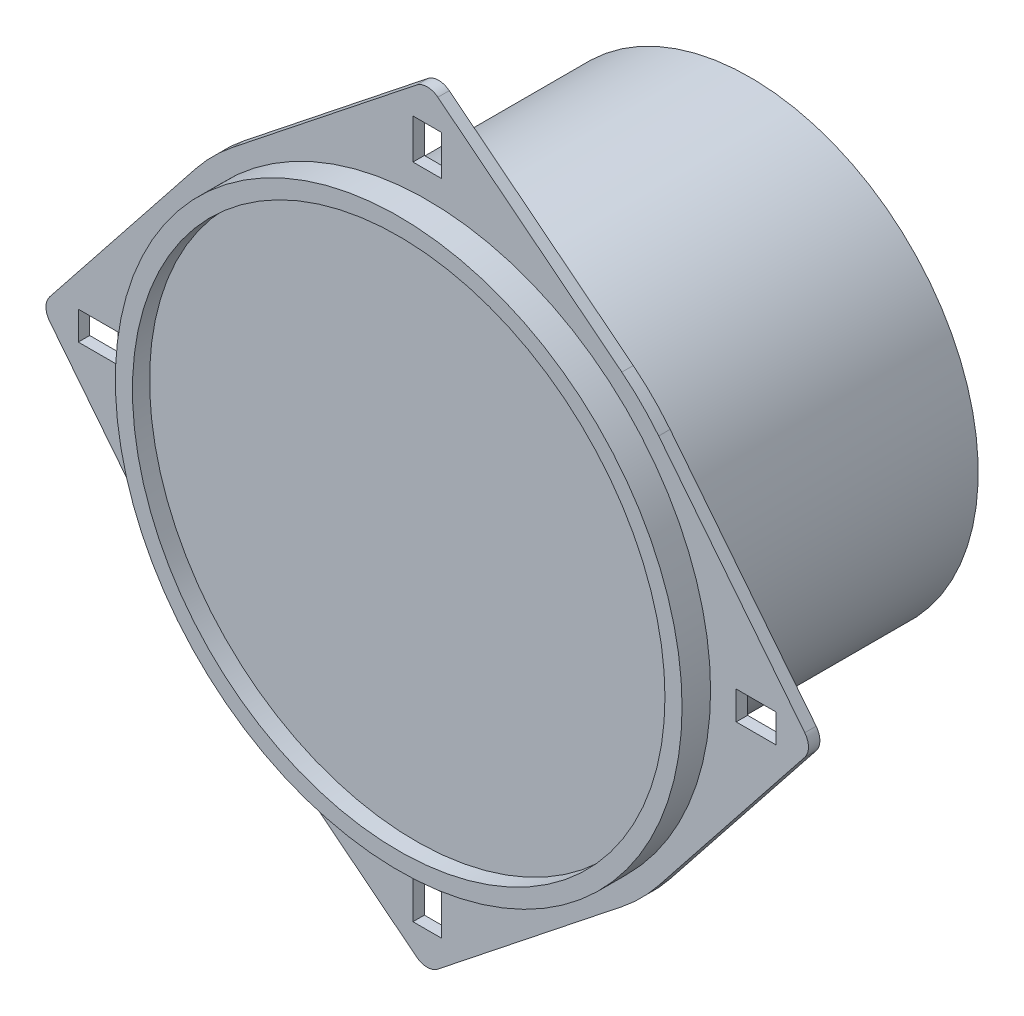
SolidWorks part; units mm, degrees
ref_plane "Front Plane" through (0, 0, 0) normal (0, 0, 1) x (1, 0, 0)
ref_plane "Top Plane" through (0, 0, 0) normal (0, 1, 0) x (1, 0, 0)
ref_plane "Right Plane" through (0, 0, 0) normal (1, 0, 0) x (0, 0, -1)
sketch "Sketch1" plane through (0, 0, 0) normal (0, 0, 1) x (1, 0, 0)
  circle A0 centre (0, 0) radius 49.685
  dimension "D1" = 99.37
extrude "Boss-Extrude1" add sketch "Sketch1" along normal blind 5
sketch "Sketch2" plane through (0, 0, 5) normal (0, 0, 1) x (1, 0, 0)
  circle A0 centre (0, 0) radius 46.685
  circle A1 centre (0, 0) radius 49.685 construction
  dimension "D1" = 3
extrude "Cut-Extrude1" cut sketch "Sketch2" against normal blind 3
sketch "Sketch3" plane through (0, 0, 0) normal (0, 0, -1) x (-1, 0, 0)
  line L0 (0, 0) -> (-57.675, 0) construction
  line L2 (0, 57.675) -> (0, 0) construction
  line L3 (0, 0) -> (57.675, 0) construction
  line L4 (-61.175, 2.5) -> (-54.175, 2.5)
  line L5 (0, 0) -> (0, -57.675) construction
  line L6 (2.5, 54.175) -> (-2.5, 54.175)
  line L7 (2.5, 54.175) -> (2.5, 61.175)
  line L8 (2.5, 61.175) -> (-2.5, 61.175)
  line L9 (-2.5, 54.175) -> (-2.5, 61.175)
  line L10 (2.5, 54.175) -> (-2.5, 61.175) construction
  line L11 (2.5, 61.175) -> (-2.5, 54.175) construction
  line L12 (61.175, -2.5) -> (54.175, -2.5)
  line L13 (61.175, -2.5) -> (61.175, 2.5)
  line L14 (61.175, 2.5) -> (54.175, 2.5)
  line L15 (54.175, -2.5) -> (54.175, 2.5)
  line L16 (61.175, -2.5) -> (54.175, 2.5) construction
  line L17 (61.175, 2.5) -> (54.175, -2.5) construction
  line L18 (-54.175, -2.5) -> (-54.175, 2.5)
  line L19 (-61.175, -2.5) -> (-54.175, -2.5)
  line L20 (-61.175, -2.5) -> (-61.175, 2.5)
  line L21 (-61.175, 2.5) -> (-54.175, -2.5) construction
  line L22 (-61.175, -2.5) -> (-54.175, 2.5) construction
  line L23 (2.5, -61.175) -> (-2.5, -54.175) construction
  line L24 (2.5, -54.175) -> (-2.5, -61.175) construction
  line L25 (-2.5, -54.175) -> (-2.5, -61.175)
  line L26 (2.5, -61.175) -> (-2.5, -61.175)
  line L27 (2.5, -54.175) -> (2.5, -61.175)
  line L28 (2.5, -54.175) -> (-2.5, -54.175)
  line L29 (0, 0) -> (-37.7277, 37.7277) construction
  line L30 (-57.675, 0) -> (-67.675, 0) construction
  line L31 (57.675, 0) -> (67.675, 0) construction
  line L32 (0, -57.675) -> (0, -67.675) construction
  line L33 (0, 57.675) -> (0, 67.675) construction
  line L34 (-37.7277, 37.7277) -> (-67.675, 0)
  line L35 (0, 0) -> (37.7277, -37.7277) construction
  line L36 (-67.675, 0) -> (-37.7277, -37.7277)
  line L37 (37.7277, 37.7277) -> (0, 0) construction
  line L38 (0, 0) -> (-37.7277, -37.7277) construction
  line L39 (-37.7277, -37.7277) -> (0, -67.675)
  line L40 (0, -67.675) -> (37.7277, -37.7277)
  line L41 (37.7277, -37.7277) -> (67.675, 0)
  line L42 (67.675, 0) -> (37.7277, 37.7277)
  line L43 (37.7277, 37.7277) -> (0, 67.675)
  line L44 (0, 67.675) -> (-37.7277, 37.7277)
  circle A0 centre (0, 0) radius 53.355 construction
  dimension "D4" = 106.71
  dimension "D1" = 5
  dimension "D2" = 108.35
  dimension "D3" = 7
  dimension "D6" = 10
extrude "Boss-Extrude2" add sketch "Sketch3" along normal blind 2
sketch "Sketch4" plane through (0, 0, -2) normal (0, 0, -1) x (-1, 0, 0)
  circle A0 centre (0, 0) radius 40
  dimension "D1" = 80
extrude "Boss-Extrude3" add sketch "Sketch4" along normal blind 54.61
fillet "Fillet2" radius 3 4 edges at (-67.675, 0, -1) (0, 67.675, -1) (67.675, 0, -1) (0, -67.675, -1)
fillet "Fillet3" radius 40 4 edges at (-37.7277, 37.7277, -1) (37.7277, 37.7277, -1) (37.7277, -37.7277, -1) (-37.7277, -37.7277, -1)
